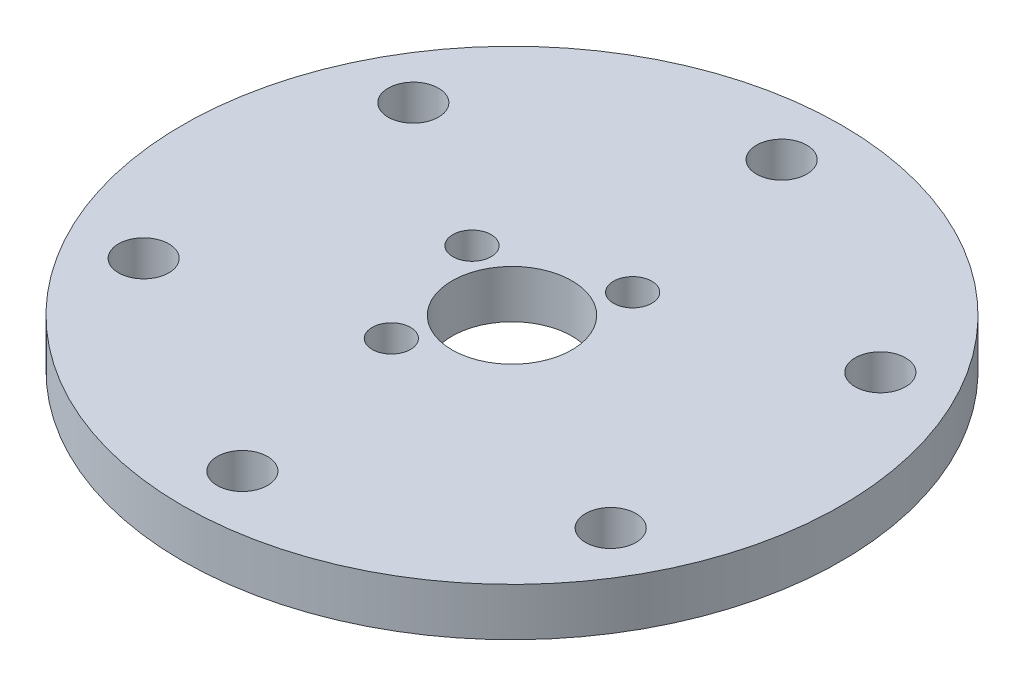
SolidWorks part; units mm, degrees
ref_plane "Front Plane" through (0, 0, 0) normal (0, 0, 1) x (1, 0, 0)
ref_plane "Top Plane" through (0, 0, 0) normal (0, 1, 0) x (1, 0, 0)
ref_plane "Right Plane" through (0, 0, 0) normal (1, 0, 0) x (0, 0, -1)
sketch "Sketch1" plane through (0, 0, 0) normal (0, 1, 0) x (1, 0, 0)
  line L0 (0, 22.5) -> (0, 0) construction
  circle A0 centre (0, 0) radius 27.5
  circle A1 centre (0, 22.5) radius 2.1
  circle A2 centre (19.4856, 11.25) radius 2.1
  circle A3 centre (19.4856, -11.25) radius 2.1
  circle A4 centre (0, -22.5) radius 2.1
  circle A5 centre (-19.4856, -11.25) radius 2.1
  circle A6 centre (-19.4856, 11.25) radius 2.1
  circle A7 centre (0, 0) radius 5
  point P18 (0, 0)
  point P25 (0, 0)
  dimension "D1" = 55
  dimension "D2" = 4.2
  dimension "D5" = 10
  dimension "D4" = 22.5
  dimension "D3" = 6
extrude "Boss-Extrude1" add sketch "Sketch1" along normal blind 4
sketch "Sketch2" plane through (0, 0, 0) normal (0, -1, 0) x (1, 0, 0)
  circle A0 centre (3.3657, -6.7024) radius 1.6 construction
  circle A1 centre (-6.7024, -3.3657) radius 1.6 construction
  circle A2 centre (-3.3657, 6.7024) radius 1.6 construction
  circle A3 centre (3.3657, -6.7024) radius 1.6
  circle A4 centre (-6.7024, -3.3657) radius 1.6
  circle A5 centre (-3.3657, 6.7024) radius 1.6
extrude "Cut-Extrude1" cut sketch "Sketch2" against normal through all
